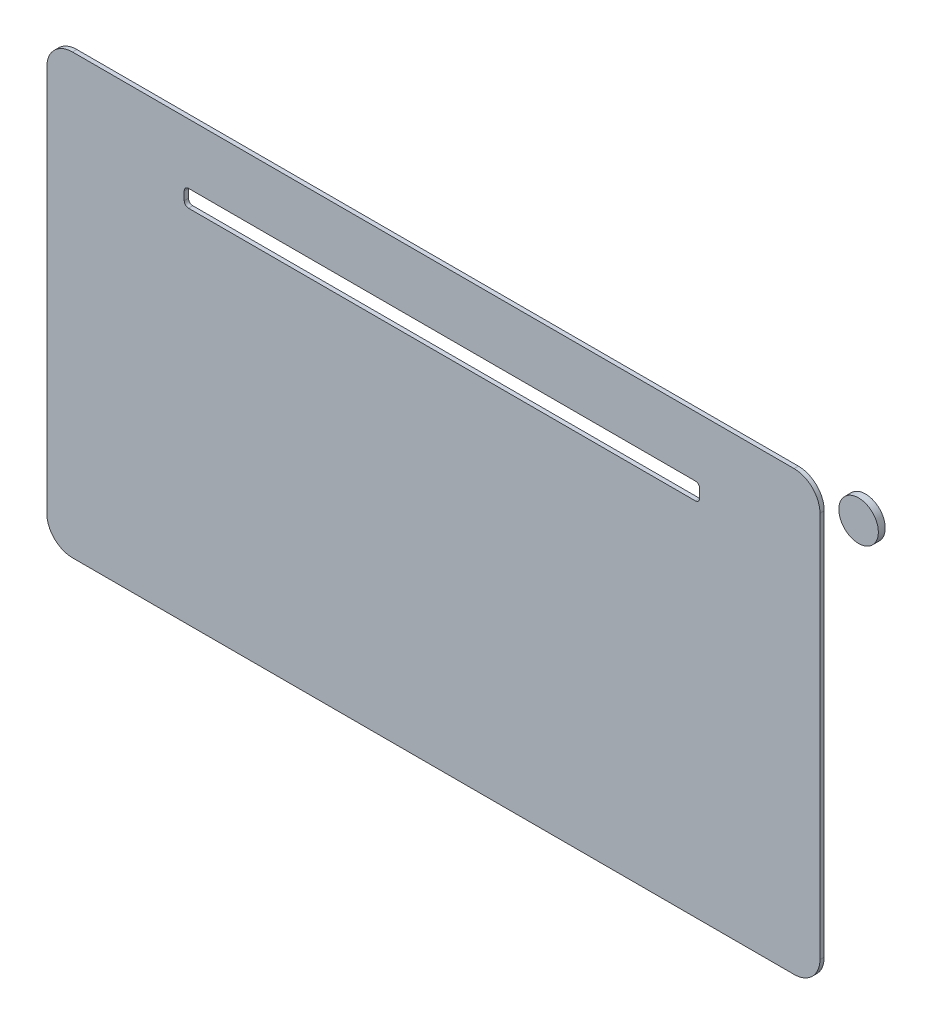
SolidWorks part; units mm, degrees
ref_plane "前视基准面" through (0, 0, 0) normal (0, 0, 1) x (1, 0, 0)
ref_plane "上视基准面" through (0, 0, 0) normal (0, 1, 0) x (1, 0, 0)
ref_plane "右视基准面" through (0, 0, 0) normal (1, 0, 0) x (0, 0, -1)
other "Configuration Table"
sketch "草图1" plane through (0, 0, 0) normal (0, 0, 1) x (1, 0, 0)
  line L0 (41, 12) -> (125, 12)
  line L1 (128, 15) -> (128, 60)
  line L2 (125, 63) -> (41, 63)
  line L3 (38, 60) -> (38, 15)
  arc A0 (125, 12) -> (128, 15) centre (125, 15) ccw
  arc A1 (128, 60) -> (125, 63) centre (125, 60) ccw
  arc A2 (41, 63) -> (38, 60) centre (41, 60) ccw
  arc A3 (38, 15) -> (41, 12) centre (41, 15) ccw
extrude "Printer_access_door_outside_case" add sketch "草图1" along normal blind 0.5 from offset 0.5
sketch "草图2" plane through (0, 0, 0) normal (0, 0, 1) x (1, 0, 0)
  circle A0 centre (132.5, 61.5) radius 2.3
extrude "Printer_feed_button" add sketch "草图2" along normal blind 0.8 from offset 0.8 separate body
sketch "草图3" plane through (0, 0, -0.5) normal (0, 0, -1) x (-1, 0, 0)
  line L0 (-113.5, 54) -> (-54.5, 54)
  line L1 (-54, 54.5) -> (-54, 55.5)
  line L2 (-54.5, 56) -> (-113.5, 56)
  line L3 (-114, 55.5) -> (-114, 54.5)
  arc A0 (-54.5, 54) -> (-54, 54.5) centre (-54.5, 54.5) ccw
  arc A1 (-54, 55.5) -> (-54.5, 56) centre (-54.5, 55.5) ccw
  arc A2 (-113.5, 56) -> (-114, 55.5) centre (-113.5, 55.5) ccw
  arc A3 (-114, 54.5) -> (-113.5, 54) centre (-113.5, 54.5) ccw
extrude "Visible_paper_output_slot_REFERENCE" cut sketch "草图3" against normal blind 1
